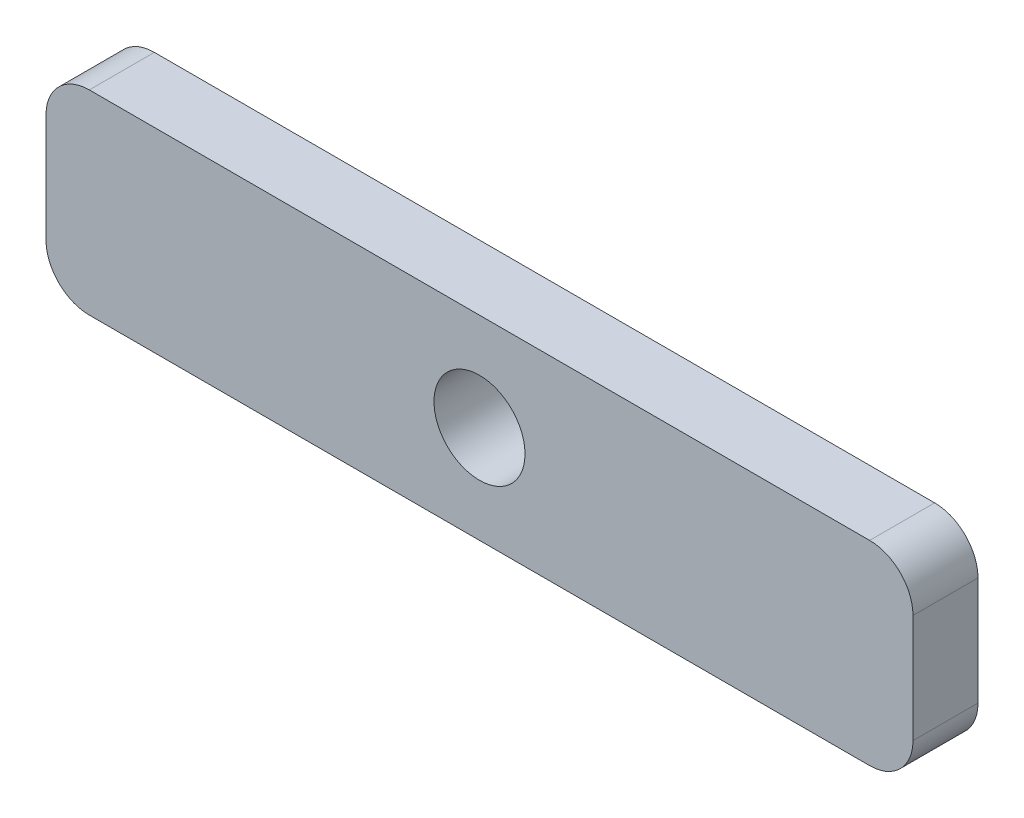
SolidWorks part; units mm, degrees
ref_plane "前视基准面" through (0, 0, 0) normal (0, 0, 1) x (1, 0, 0)
ref_plane "上视基准面" through (0, 0, 0) normal (0, 1, 0) x (1, 0, 0)
ref_plane "右视基准面" through (0, 0, 0) normal (1, 0, 0) x (0, 0, -1)
sketch "草图1" plane through (0, 0, 0) normal (0, 0, 1) x (1, 0, 0)
  line L1 (-20, 4.5) -> (20, 4.5)
  line L2 (-20, 4.5) -> (-20, -4.5)
  line L3 (-20, -4.5) -> (20, -4.5)
  line L4 (20, 4.5) -> (20, -4.5)
  line L5 (-20, 4.5) -> (20, -4.5) construction
  line L6 (-20, -4.5) -> (20, 4.5) construction
  circle A0 centre (0, 0) radius 2.1
  point P4 (0, 0)
  dimension "D3" = 4.2
  dimension "D1" = 40
  dimension "D2" = 9
extrude "凸台-拉伸1" add sketch "草图1" along normal blind 3
fillet "圆角1" radius 2 4 edges at (20, -4.5, 1.5) (-20, -4.5, 1.5) (20, 4.5, 1.5) (-20, 4.5, 1.5)
